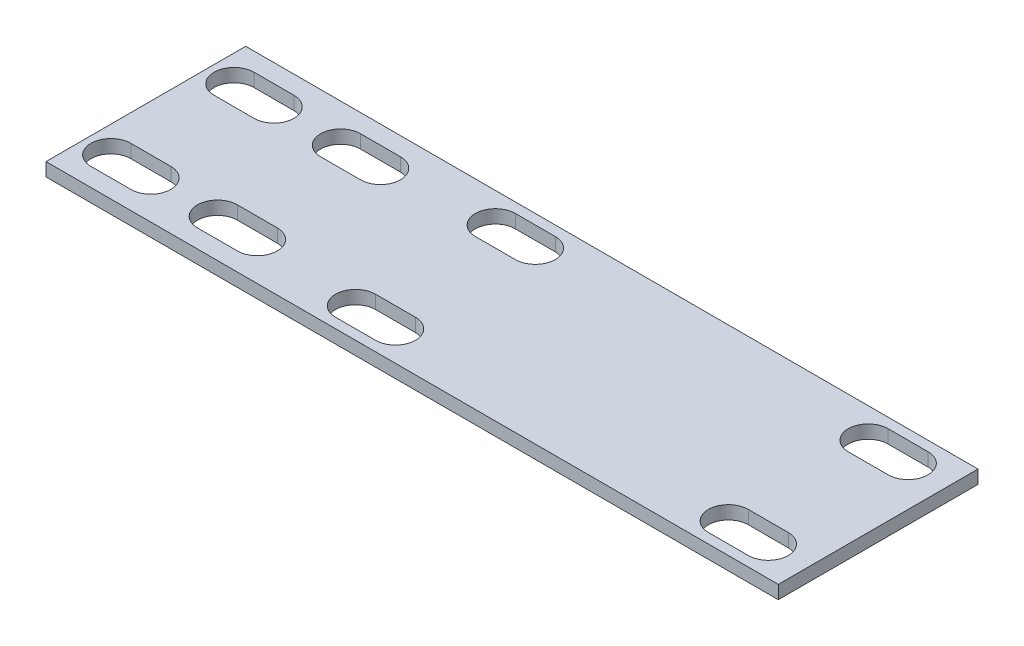
SolidWorks part; units mm, degrees
ref_plane "前视基准面" through (0, 0, 0) normal (0, 0, 1) x (1, 0, 0)
ref_plane "上视基准面" through (0, 0, 0) normal (0, 1, 0) x (1, 0, 0)
ref_plane "右视基准面" through (0, 0, 0) normal (1, 0, 0) x (0, 0, -1)
other "Configuration Table"
sketch "草图1" plane through (0, 0, 0) normal (0, 1, 0) x (1, 0, 0)
  line L1 (0, 0) -> (110, 0)
  line L2 (0, 0) -> (0, 30)
  line L3 (0, 30) -> (110, 30)
  line L4 (110, 0) -> (110, 30)
  line L5 (0, 15) -> (0, 0)
  line L6 (0, 15) -> (0, 0)
  line L7 (0, 15) -> (0, 5.75)
  line L8 (98, 25.5) -> (104, 25.5) construction
  line L9 (4, 5.75) -> (10, 5.75) construction
  line L10 (4, 8.75) -> (10, 8.75)
  line L11 (4, 2.75) -> (10, 2.75)
  line L12 (98, 22.5) -> (104, 22.5)
  line L13 (20, 5.75) -> (26, 5.75) construction
  line L14 (20, 8.75) -> (26, 8.75)
  line L15 (20, 2.75) -> (26, 2.75)
  line L16 (98, 28.5) -> (104, 28.5)
  line L17 (42, 25.5) -> (48, 25.5) construction
  line L18 (42, 22.5) -> (48, 22.5)
  line L19 (42, 28.5) -> (48, 28.5)
  line L20 (20, 24.25) -> (26, 24.25) construction
  line L21 (42, 4.5) -> (48, 4.5) construction
  line L22 (42, 7.5) -> (48, 7.5)
  line L23 (42, 1.5) -> (48, 1.5)
  line L24 (20, 21.25) -> (26, 21.25)
  line L25 (98, 4.5) -> (104, 4.5) construction
  line L26 (98, 7.5) -> (104, 7.5)
  line L27 (98, 1.5) -> (104, 1.5)
  line L28 (20, 27.25) -> (26, 27.25)
  line L29 (4, 24.25) -> (10, 24.25) construction
  line L30 (4, 21.25) -> (10, 21.25)
  line L31 (4, 27.25) -> (10, 27.25)
  arc A0 (4, 8.75) -> (4, 2.75) centre (4, 5.75) ccw
  arc A1 (10, 2.75) -> (10, 8.75) centre (10, 5.75) ccw
  arc A2 (20, 8.75) -> (20, 2.75) centre (20, 5.75) ccw
  arc A3 (26, 2.75) -> (26, 8.75) centre (26, 5.75) ccw
  arc A4 (42, 7.5) -> (42, 1.5) centre (42, 4.5) ccw
  arc A5 (48, 1.5) -> (48, 7.5) centre (48, 4.5) ccw
  arc A6 (98, 7.5) -> (98, 1.5) centre (98, 4.5) ccw
  arc A7 (104, 1.5) -> (104, 7.5) centre (104, 4.5) ccw
  arc A8 (98, 22.5) -> (98, 28.5) centre (98, 25.5) cw
  arc A9 (104, 28.5) -> (104, 22.5) centre (104, 25.5) cw
  arc A10 (42, 22.5) -> (42, 28.5) centre (42, 25.5) cw
  arc A11 (48, 28.5) -> (48, 22.5) centre (48, 25.5) cw
  arc A12 (20, 21.25) -> (20, 27.25) centre (20, 24.25) cw
  arc A13 (26, 27.25) -> (26, 21.25) centre (26, 24.25) cw
  arc A14 (4, 21.25) -> (4, 27.25) centre (4, 24.25) cw
  arc A15 (10, 27.25) -> (10, 21.25) centre (10, 24.25) cw
  point P5 (7, 5.75)
  point P17 (23, 5.75)
  point P24 (101, 25.5)
  point P30 (45, 4.5)
  point P37 (101, 4.5)
  point P45 (45, 25.5)
  point P52 (23, 24.25)
  point P59 (7, 24.25)
extrude "凸台-拉伸1" add sketch "草图1" along normal blind 2 contours L1 L4 L3 L2 L6 A7 L27 A6 L26 A5 L23 A4 L22 A3 L15 A2 L14 A1 L11 A0 L10 L16 A9 L12 A8 L19 A11 L18 A10 L28 A13 L24 A12 L31 A15 L30 A14
